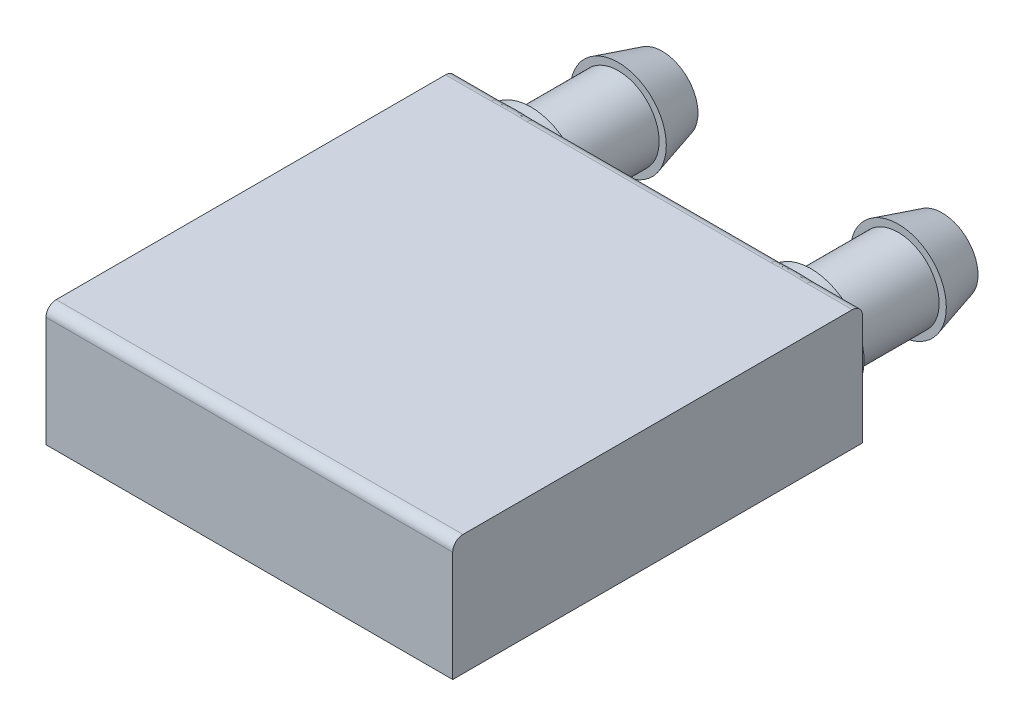
SolidWorks part; units mm, degrees
material "Plain Carbon Steel"
ref_plane "Front Plane" through (0, 0, 0) normal (0, 0, 1) x (1, 0, 0)
ref_plane "Top Plane" through (0, 0, 0) normal (0, 1, 0) x (1, 0, 0)
ref_plane "Right Plane" through (0, 0, 0) normal (1, 0, 0) x (0, 0, -1)
sketch "Sketch1" plane through (0, 0, 0) normal (0, 1, 0) x (1, 0, 0)
  line L1 (0, 0) -> (39.8, 0)
  line L2 (0, 0) -> (0, 40.1)
  line L3 (0, 40.1) -> (39.8, 40.1)
  line L4 (39.8, 0) -> (39.8, 40.1)
extrude "Boss-Extrude1" add sketch "Sketch1" along normal blind 11.8
sketch "Sketch2" plane through (0, 0, -40.1) normal (0, 0, -1) x (-1, 0, 0)
  line L0 (5.1841, 5.9) -> (-43.4873, 5.9) construction
  circle A0 centre (-6.2, 5.9) radius 5.2
  circle A1 centre (-33.6, 5.9) radius 5.2
extrude "Boss-Extrude2" add sketch "Sketch2" along normal blind 1.15
sketch "Sketch3" plane through (0, 0, -41.25) normal (0, 0, -1) x (-1, 0, 0)
  circle A0 centre (-33.6, 5.9) radius 4
  circle A1 centre (-6.2, 5.9) radius 4
extrude "Boss-Extrude3" add sketch "Sketch3" along normal blind 8.55
sketch "Sketch4" plane through (0, 0, -49.8) normal (0, 0, -1) x (-1, 0, 0)
  line L0 (-8.1851, 5.9) -> (-6.2, 5.9)
  line L1 (-6.2, 5.9) -> (-6.2, 4.3616)
  line L2 (-6.2, 4.3616) -> (-8.1851, 4.3616)
  line L3 (-8.1851, 4.3616) -> (-8.1851, 5.9)
sketch "Sketch5" plane through (0, 0, 0) normal (0, 1, 0) x (1, 0, 0)
  line L0 (6.2, 49.8) -> (6.2, 56.9697) construction
  line L1 (8.1851, 49.8) -> (6.2, 49.8) construction
  line L2 (6.2, 49.8) -> (10.9, 49.8)
  line L3 (10.9, 49.8) -> (9.7, 54.1)
  line L4 (9.7, 54.1) -> (6.2, 54.1)
  line L5 (6.2, 49.8) -> (6.2, 54.1)
extrude "Boss-Extrude4" add sketch "Sketch4" along normal blind 1
sketch "Sketch7" plane through (0, 5.9, 0) normal (0, 1, 0) x (1, 0, 0)
  line L0 (6.2, 49.8) -> (6.2, 56.9697) construction
  line L1 (6.2, 49.8) -> (10.9, 49.8)
  line L2 (10.9, 49.8) -> (9.7, 54.1)
  line L3 (9.7, 54.1) -> (6.2, 54.1)
  line L4 (6.2, 49.8) -> (6.2, 54.1)
revolve "Revolve2" add sketch "Sketch7" angle 360 about L0
sketch "Sketch10" plane through (0, 0, -49.8) normal (0, 0, -1) x (-1, 0, 0)
  line L0 (-33.6, 5.9) -> (-35.0503, 5.9)
  line L1 (-35.0503, 5.9) -> (-35.0503, 4.9326)
  line L2 (-35.0503, 4.9326) -> (-33.6, 4.9326)
  line L3 (-33.6, 4.9326) -> (-33.6, 5.9)
extrude "Boss-Extrude5" add sketch "Sketch10" along normal blind 1
sketch "Sketch11" plane through (0, 5.9, 0) normal (0, 1, 0) x (1, 0, 0)
  line L0 (33.6, 49.8) -> (33.6, 62.6491) construction
  line L1 (33.6, 49.8) -> (28.9, 49.8)
  line L2 (33.6, 49.8) -> (33.6, 54.1)
  line L3 (33.6, 54.1) -> (30.1, 54.1)
  line L4 (30.1, 54.1) -> (28.9, 49.8)
revolve "Revolve4" add sketch "Sketch11" angle 360 about L0
sketch "Sketch12" plane through (0, 0, -54.1) normal (0, 0, -1) x (-1, 0, 0)
  circle A0 centre (-6.2, 5.9) radius 3.15
  circle A1 centre (-33.6, 5.9) radius 3.15
extrude "Cut-Extrude1" cut sketch "Sketch12" against normal blind 15
fillet "Fillet1" radius 1 2 edges at (19.9, 11.8, 0) (19.9, 11.8, -40.1)
